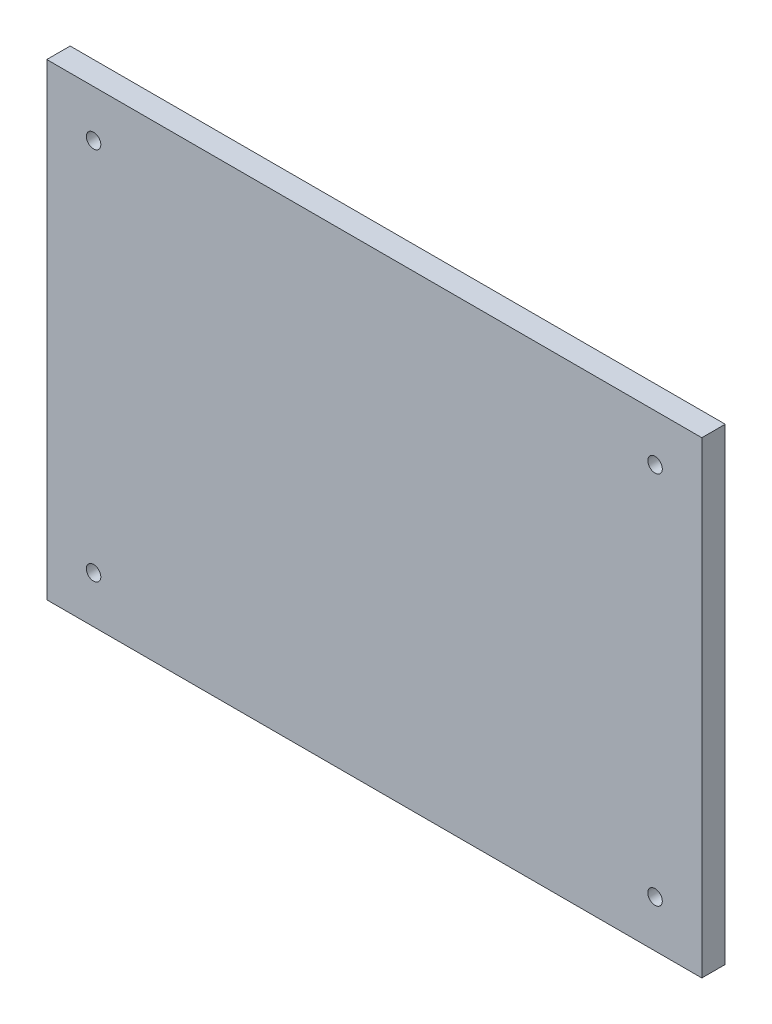
SolidWorks part; units mm, degrees
ref_plane "Plan de face" through (0, 0, 0) normal (0, 0, 1) x (1, 0, 0)
ref_plane "Plan de dessus" through (0, 0, 0) normal (0, 1, 0) x (1, 0, 0)
ref_plane "Plan de droite" through (0, 0, 0) normal (1, 0, 0) x (0, 0, -1)
sketch "Esquisse1" plane through (0, 0, 0) normal (0, 0, 1) x (1, 0, 0)
  line L0 (0, 0) -> (0, 37.8608) construction
  line L1 (-70, -50) -> (70, -50)
  line L2 (-70, -50) -> (-70, 50)
  line L3 (-70, 50) -> (70, 50)
  line L4 (70, -50) -> (70, 50)
  line L5 (-70, -50) -> (70, 50) construction
  line L6 (-70, 50) -> (70, -50) construction
  line L7 (0, 0) -> (30.7246, 0) construction
  circle A0 centre (-60, -40) radius 1.55
  circle A1 centre (60, -40) radius 1.55
  circle A2 centre (60, 40) radius 1.55
  circle A3 centre (-60, 40) radius 1.55
  point P0 (0, 0)
  dimension "D3" = 3.1
  dimension "D1" = 140
  dimension "D2" = 100
  dimension "D4" = 10
  dimension "D5" = 10
extrude "Boss.-Extru.1" add sketch "Esquisse1" against normal blind 5
